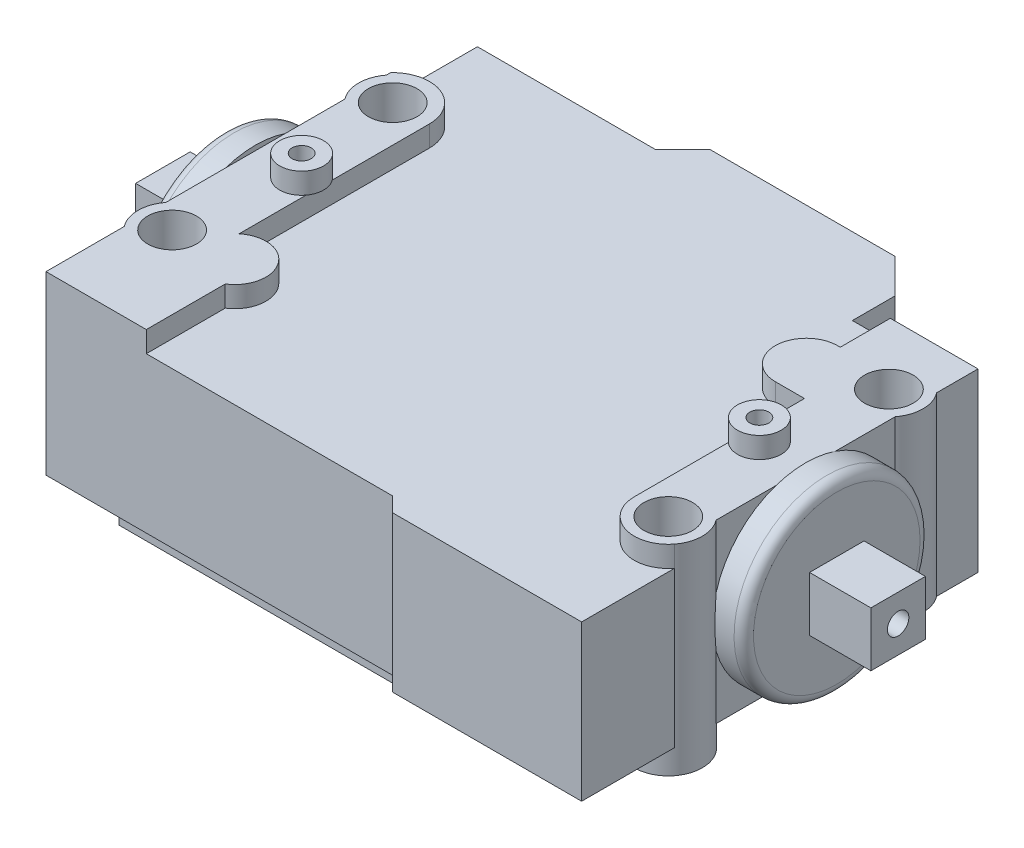
SolidWorks part; units mm, degrees
ref_plane "Front Plane" through (0, 0, 0) normal (0, 0, 1) x (1, 0, 0)
ref_plane "Top Plane" through (0, 0, 0) normal (0, 1, 0) x (1, 0, 0)
ref_plane "Right Plane" through (0, 0, 0) normal (1, 0, 0) x (0, 0, -1)
sketch "Sketch1" plane through (0, 0, 0) normal (1, 0, 0) x (0, 0, -1)
  line L1 (-2.8, -2.8) -> (2.8, -2.8)
  line L2 (-2.8, -2.8) -> (-2.8, 2.8)
  line L3 (-2.8, 2.8) -> (2.8, 2.8)
  line L4 (2.8, -2.8) -> (2.8, 2.8)
  line L5 (-2.8, -2.8) -> (2.8, 2.8) construction
  line L6 (-2.8, 2.8) -> (2.8, -2.8) construction
  circle A0 centre (0, 0) radius 1.1
  point P0 (0, 0)
  dimension "D2" = 2.2
  dimension "D1" = 5.6
extrude "Boss-Extrude1" add sketch "Sketch1" along normal mid plane 75.5
sketch "Sketch2" plane through (0, 0, 0) normal (0, 1, 0) x (1, 0, 0)
  line L0 (8.85, -23) -> (28.25, -23)
  line L1 (28.25, -23) -> (28.25, 17.7)
  line L2 (28.25, 17.7) -> (15.35, 17.7)
  line L3 (15.35, 17.7) -> (15.35, 22.1)
  line L4 (15.35, 22.1) -> (11.85, 25.6)
  line L5 (11.85, 25.6) -> (-7.15, 25.6)
  line L6 (-7.15, 25.6) -> (-9.95, 22.8)
  line L7 (-9.95, 22.8) -> (-28.25, 22.8)
  line L8 (-28.25, 22.8) -> (-28.25, -21.5)
  line L9 (8.85, -23) -> (7.35, -21.5)
  line L10 (7.35, -21.5) -> (-28.25, -21.5)
  line L11 (37.75, -2.8) -> (-37.75, -2.8) construction
  line L12 (-28.25, 0) -> (28.25, 0) construction
  line L13 (37.75, 2.8) -> (-37.75, 2.8) construction
  point P5 (0.7338, -19.1145)
  dimension "D1" = 16.4
  dimension "D2" = 7.9
  dimension "D3" = 56.5
  dimension "D4" = 18.7
  dimension "D5" = 19.4
  dimension "D6" = 1.5
  dimension "D7" = 45
  dimension "D8" = 14.9
  dimension "D9" = 12.9
  dimension "D10" = 44.3
  dimension "D11" = 19
extrude "Boss-Extrude2" add sketch "Sketch2" along normal mid plane 18.1
sketch "Sketch4" plane through (0, 9.05, 0) normal (0, 1, 0) x (1, 0, 0)
  line L1 (25.475, -11.325) -> (-25.475, -11.325) construction
  line L2 (25.475, -11.325) -> (25.475, 11.325) construction
  line L3 (25.475, 11.325) -> (-25.475, 11.325) construction
  line L4 (-25.475, -11.325) -> (-25.475, 11.325) construction
  line L5 (25.475, -11.325) -> (-25.475, 11.325) construction
  line L6 (25.475, 11.325) -> (-25.475, -11.325) construction
  circle A0 centre (-25.475, 11.325) radius 3.5
  circle A1 centre (-25.475, -11.325) radius 3.5
  circle A2 centre (25.475, -11.325) radius 3.5
  circle A3 centre (25.475, 11.325) radius 3.5
  point P0 (0, 0)
  dimension "D1" = 7
  dimension "D2" = 50.95
  dimension "D3" = 22.65
extrude "Boss-Extrude4" add sketch "Sketch4" against normal up to surface (18.1 mm away) up to face at (3.7864, -9.05, -5.9364)
sketch "Sketch5" plane through (0, -9.05, 0) normal (0, -1, 0) x (1, 0, 0)
  circle A0 centre (-25.475, 11.325) radius 3.5
  circle A1 centre (25.475, 11.325) radius 3.5
  arc A2 (-28.25, 13.4579) -> (-28.25, 9.1921) centre (-25.475, 11.325) ccw construction
  arc A3 (28.25, 9.1921) -> (28.25, 13.4579) centre (25.475, 11.325) ccw construction
extrude "Boss-Extrude5" add sketch "Sketch5" along normal blind 2.5
sketch "Sketch6" plane through (0, 9.05, 0) normal (0, 1, 0) x (1, 0, 0)
  circle A0 centre (-25.475, 11.325) radius 2.5
  circle A1 centre (25.475, 11.325) radius 2.5
  circle A2 centre (25.475, -11.325) radius 2.5
  circle A3 centre (-25.475, -11.325) radius 2.5
  dimension "D1" = 5
extrude "Cut-Extrude1" cut sketch "Sketch6" against normal blind 19.2
sketch "Sketch7" plane through (0, -10.15, 0) normal (0, 1, 0) x (1, 0, 0)
  circle A0 centre (-25.475, -11.325) radius 1.35
  circle A1 centre (25.475, -11.325) radius 1.35
  dimension "D1" = 2.7
extrude "Cut-Extrude2" cut sketch "Sketch7" against normal through all
sketch "Sketch8" plane through (0, -9.05, 0) normal (0, -1, 0) x (1, 0, 0)
  line L0 (-21.25, 21) -> (21.25, 21)
  line L1 (21.25, 21) -> (21.25, -8.2)
  line L2 (21.25, -8.2) -> (4.7975, -8.2)
  line L3 (4.7975, -8.2) -> (4.7975, -21.3)
  line L4 (4.7975, -21.3) -> (-21.25, -21.3)
  line L5 (-21.25, -21.3) -> (-21.25, 21)
  line L6 (-28.25, 21.5) -> (7.35, 21.5) construction
  line L7 (28.25, -17.7) -> (15.35, -17.7) construction
  line L8 (-9.95, -22.8) -> (-28.25, -22.8) construction
  line L9 (-19.75, -19.8) -> (-19.75, 19.5)
  line L10 (-19.75, 19.5) -> (19.75, 19.5)
  line L11 (19.75, 19.5) -> (19.75, -6.7)
  line L12 (19.75, -6.7) -> (3.2975, -6.7)
  line L13 (3.2975, -6.7) -> (3.2975, -19.8)
  line L14 (3.2975, -19.8) -> (-19.75, -19.8)
  point P4 (0, 21)
  dimension "D1" = 42.5
  dimension "D2" = 0.5
  dimension "D3" = 16.4525
  dimension "D4" = 9.5
  dimension "D5" = 1.5
  dimension "D6" = 1.5
extrude "Boss-Extrude6" add sketch "Sketch8" along normal blind 1.2
sketch "Sketch3" plane through (28.25, 0, 0) normal (1, 0, 0) x (0, 0, -1)
  circle A0 centre (0, 0) radius 9.55
  dimension "D1" = 19.1
extrude "Boss-Extrude3" add sketch "Sketch3" along normal blind 3.2
fillet "Fillet1" radius 1 1 edges at (31.45, 0, -9.55)
mirror "Mirror1" about plane through (0, 0, 0) normal (1, 0, 0) of "Boss-Extrude3", "Fillet1"
sketch "Sketch9" plane through (0, 9.05, 0) normal (0, 1, 0) x (1, 0, 0)
  line L0 (-23.5, 0) -> (23.5, 0) construction
  circle A0 centre (-23.5, 0) radius 0.975
  circle A1 centre (-23.5, 0) radius 2.25
  circle A2 centre (23.5, 0) radius 0.975
  circle A3 centre (23.5, 0) radius 2.25
  dimension "D1" = 4.5
  dimension "D2" = 1.95
  dimension "D3" = 47
extrude "Boss-Extrude7" add sketch "Sketch9" along normal blind 2.15
sketch "Sketch10" plane through (0, 9.05, 0) normal (0, 1, 0) x (1, 0, 0)
  line L0 (-17.95, -34.9077) -> (-17.95, -13.395)
  line L2 (-28.25, -13.4579) -> (-28.25, -21.5) construction
  line L3 (-21.7, -8.2228) -> (-21.7, 11.325)
  line L4 (-28.25, 22.8) -> (-28.25, 13.4579) construction
  line L5 (-28.25, 13.8843) -> (-28.25, 32.6644)
  line L6 (-25.475, -11.325) -> (25.475, 11.325) construction
  line L7 (-8.6929, 19.5542) -> (8.6929, -19.5542) construction
  line L8 (19.25, 12.5453) -> (19.25, 32.6644)
  line L9 (18.975, 6.1571) -> (21.975, 6.1571)
  line L10 (19.25, 32.6644) -> (-28.25, 32.6644)
  line L11 (28.25, 13.4579) -> (28.25, 17.7) construction
  line L13 (21.975, 6.1571) -> (21.975, -11.325)
  line L16 (28.25, -13.4579) -> (28.25, -34.9077)
  line L17 (28.25, -34.9077) -> (-17.95, -34.9077)
  arc A0 (-21.7, -8.2228) -> (-17.95, -13.395) centre (-19.6703, -10.6967) cw
  arc A1 (-21.7, 11.325) -> (-28.25, 13.8843) centre (-25.475, 11.325) ccw
  circle A2 centre (-25.475, 11.325) radius 2.5 construction
  circle A3 centre (-23.5, 0) radius 2.25 construction
  arc A4 (21.975, -11.325) -> (28.25, -13.4579) centre (25.475, -11.325) ccw
  arc A6 (18.975, 6.1571) -> (19.25, 12.5453) centre (18.975, 9.3571) cw
  dimension "D1" = 3.2
  dimension "D2" = 10.3
  dimension "D3" = 1.8
  dimension "D4" = 9
extrude "Cut-Extrude3" cut sketch "Sketch10" against normal blind 2.15
sketch "Sketch11" plane through (0, 11.2, 0) normal (0, 1, 0) x (1, 0, 0)
  circle A0 centre (-23.5, 0) radius 0.975 construction
  circle A1 centre (23.5, 0) radius 0.975 construction
  circle A2 centre (-23.5, 0) radius 0.975
  circle A3 centre (23.5, 0) radius 0.975
extrude "Cut-Extrude4" cut sketch "Sketch11" against normal blind 4.064
